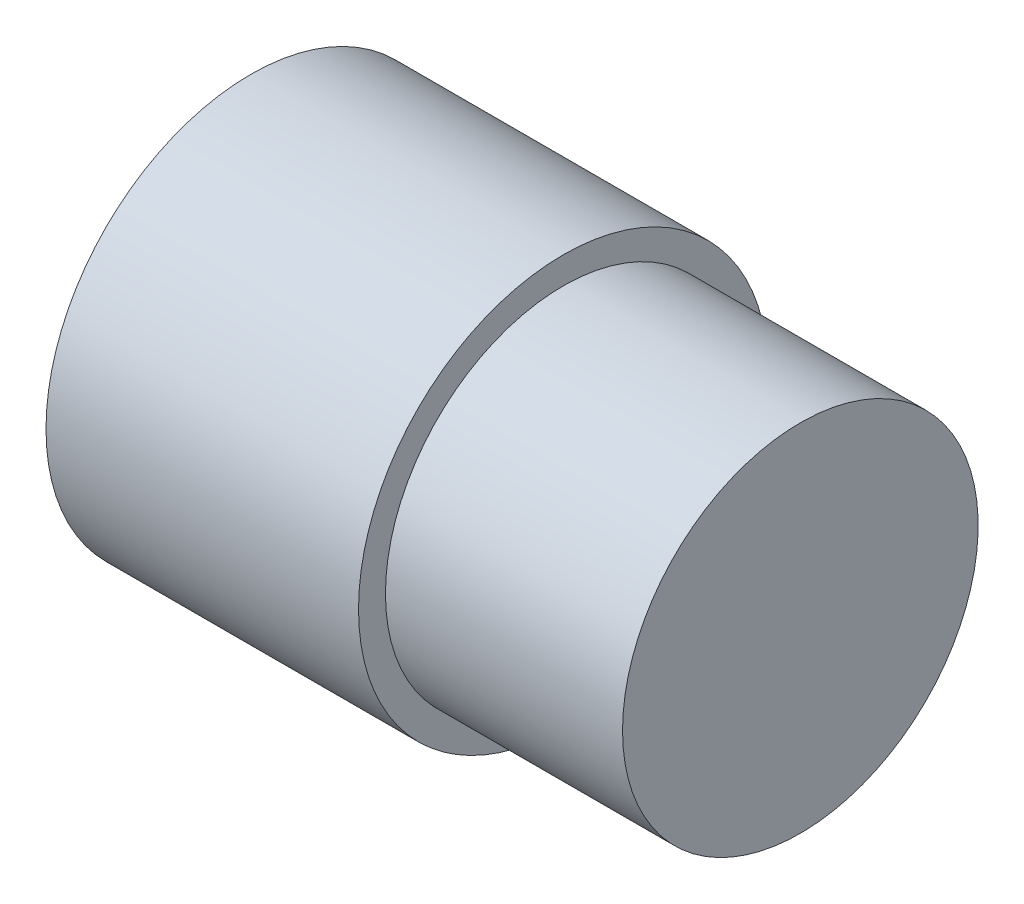
SolidWorks part; units mm, degrees
ref_plane "Front Plane" through (0, 0, 0) normal (0, 0, 1) x (1, 0, 0)
ref_plane "Top Plane" through (0, 0, 0) normal (0, 1, 0) x (1, 0, 0)
ref_plane "Right Plane" through (0, 0, 0) normal (1, 0, 0) x (0, 0, -1)
sketch "Sketch1" plane through (0, 0, 0) normal (0, 1, 0) x (1, 0, 0)
  line L0 (-14.5, 0) -> (36.5, 0)
  line L1 (-14.5, -19) -> (14.5, -19)
  line L2 (-14.5, -19) -> (-14.5, 19)
  line L3 (-14.5, 19) -> (14.5, 19)
  line L4 (14.5, -19) -> (14.5, 19)
  line L5 (-14.5, -19) -> (14.5, 19) construction
  line L6 (-14.5, 19) -> (14.5, -19) construction
  line L7 (14.5, 16.5) -> (36.5, 16.5)
  line L8 (14.5, 16.5) -> (14.5, -16.5)
  line L9 (14.5, -16.5) -> (36.5, -16.5)
  line L10 (36.5, 16.5) -> (36.5, -16.5)
  point P0 (0, 0)
  point P11 (36.5, 0)
  dimension "D1" = 29
  dimension "D2" = 22
  dimension "D3" = 33
  dimension "D4" = 38
revolve "Revolve2" add sketch "Sketch1" angle 360 about L0
